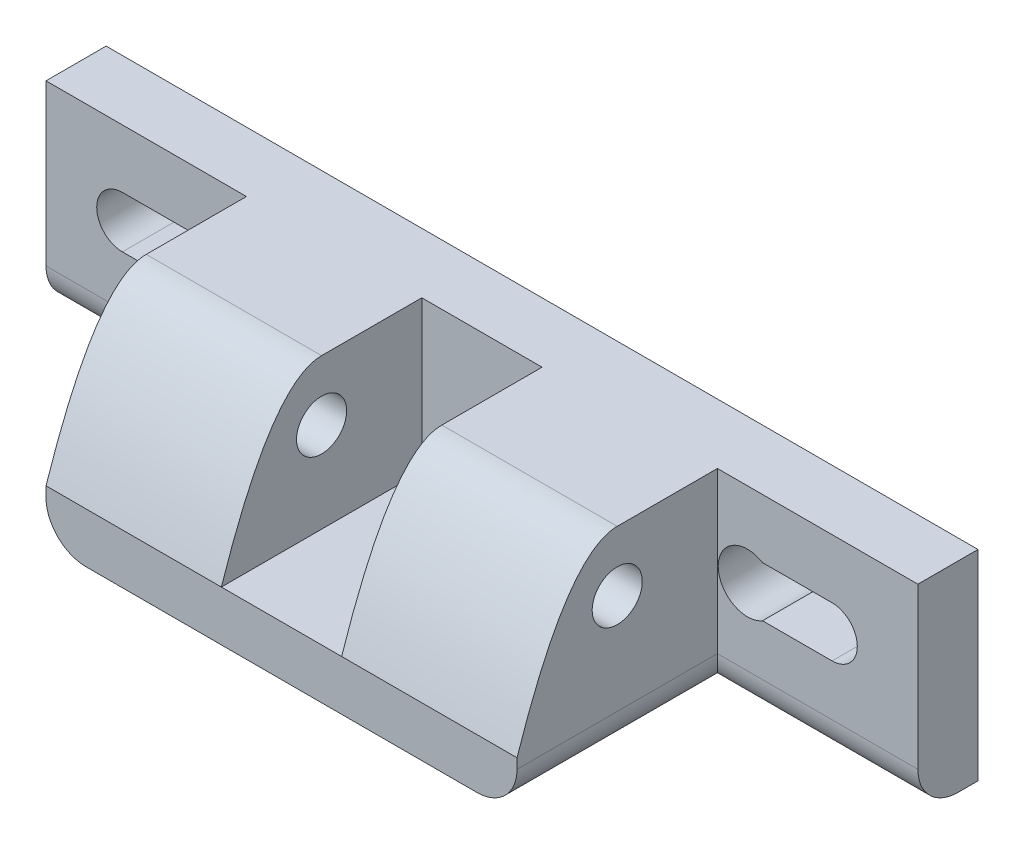
SolidWorks part; units mm, degrees
ref_plane "Front Plane" through (0, 0, 0) normal (0, 0, 1) x (1, 0, 0)
ref_plane "Top Plane" through (0, 0, 0) normal (0, 1, 0) x (1, 0, 0)
ref_plane "Right Plane" through (0, 0, 0) normal (1, 0, 0) x (0, 0, -1)
sketch "Sketch1" plane through (0, 0, 0) normal (0, 1, 0) x (1, 0, 0)
  line L1 (29.845, -12.7) -> (-29.845, -12.7)
  line L2 (29.845, -12.7) -> (29.845, 12.7)
  line L3 (29.845, 12.7) -> (-29.845, 12.7)
  line L4 (-29.845, -12.7) -> (-29.845, 12.7)
  line L5 (29.845, -12.7) -> (-29.845, 12.7) construction
  line L6 (29.845, 12.7) -> (-29.845, -12.7) construction
  point P0 (0, 0)
  dimension "D1" = 59.69
  dimension "D2" = 25.4
extrude "Boss-Extrude1" add sketch "Sketch1" along normal blind 25.4
sketch "Sketch2" plane through (0, 25.4, 0) normal (0, 1, 0) x (1, 0, 0)
  line L0 (29.845, 12.7) -> (-29.845, 12.7) construction
  line L1 (7.62, -12.7) -> (-7.62, -12.7)
  line L2 (7.62, -12.7) -> (7.62, 12.7)
  line L3 (7.62, 12.7) -> (-7.62, 12.7)
  line L4 (-7.62, -12.7) -> (-7.62, 12.7)
  line L5 (7.62, -12.7) -> (-7.62, 12.7) construction
  line L6 (7.62, 12.7) -> (-7.62, -12.7) construction
  point P0 (0, 0)
  dimension "D1" = 15.24
extrude "Cut-Extrude1" cut sketch "Sketch2" against normal blind 19.05
sketch "Sketch3" plane through (-29.845, 0, 0) normal (-1, 0, 0) x (0, 0, 1)
  line L0 (-12.7, 25.4) -> (12.7, 25.4) construction
  circle A0 centre (0, 17.78) radius 3.175
  dimension "D1" = 6.35
  dimension "D2" = 7.62
extrude "Cut-Extrude2" cut sketch "Sketch3" against normal through all
sketch "Sketch4" plane through (29.845, 0, 0) normal (1, 0, 0) x (0, 0, -1)
  line L5 (-12.7, 25.4) -> (12.7, 25.4) construction
  line L6 (-12.7, 6.35) -> (-12.7, 25.4)
  line L7 (-12.7, 25.4) -> (0, 25.4)
  spline S0 degree 2 poles (-12.7, 6.35) (-6.35, 25.4) (0, 25.4) knots 0 0 0 0.5 0.5 0.5
sketch "Sketch5" plane through (0, 0, -12.7) normal (0, 0, -1) x (-1, 0, 0)
  line L0 (29.845, 25.4) -> (29.845, 0) construction
  line L1 (-55.245, 25.4) -> (55.245, 25.4)
  line L2 (-55.245, 25.4) -> (-55.245, 0)
  line L3 (-55.245, 0) -> (55.245, 0)
  line L4 (55.245, 25.4) -> (55.245, 0)
  line L5 (-29.845, 25.4) -> (-29.845, 0) construction
  dimension "D1" = 25.4
  dimension "D2" = 25.4
  dimension "D3" = 25.4
extrude "Boss-Extrude2" add sketch "Sketch5" along normal blind 7.62
sketch "Sketch6" plane through (0, 0, -20.32) normal (0, 0, -1) x (-1, 0, 0)
  line L0 (-55.245, 25.4) -> (-55.245, 0) construction
  line L1 (55.245, 0) -> (55.245, 25.4) construction
  line L4 (-44.3774, 17.9215) -> (-35.56, 17.9215)
  line L5 (-44.3774, 11.5425) -> (-35.56, 11.5425)
  line L7 (35.56, 17.9948) -> (45.5561, 17.9948)
  line L8 (35.56, 11.4692) -> (45.5561, 11.4692)
  arc A2 (-44.3774, 17.9215) -> (-44.3774, 11.5425) centre (-44.3774, 14.732) ccw
  arc A3 (-35.56, 11.5425) -> (-35.56, 17.9215) centre (-33.655, 14.732) ccw
  arc A4 (35.56, 17.9948) -> (35.56, 11.4692) centre (33.655, 14.732) ccw
  arc A5 (45.5561, 11.4692) -> (45.5561, 17.9948) centre (45.5561, 14.732) ccw
  point P12 (-44.5796, 14.732)
  point P17 (44.561, 14.732)
  dimension "D1" = 21.59
  dimension "D2" = 21.59
extrude "Cut-Extrude4" cut sketch "Sketch4" against normal through all
extrude "Cut-Extrude5" cut sketch "Sketch6" against normal through all
fillet "Fillet2" radius 5.08 4 edges
fillet "Fillet3" radius 2.54 1 edges at (0, 6.35, -12.7)
